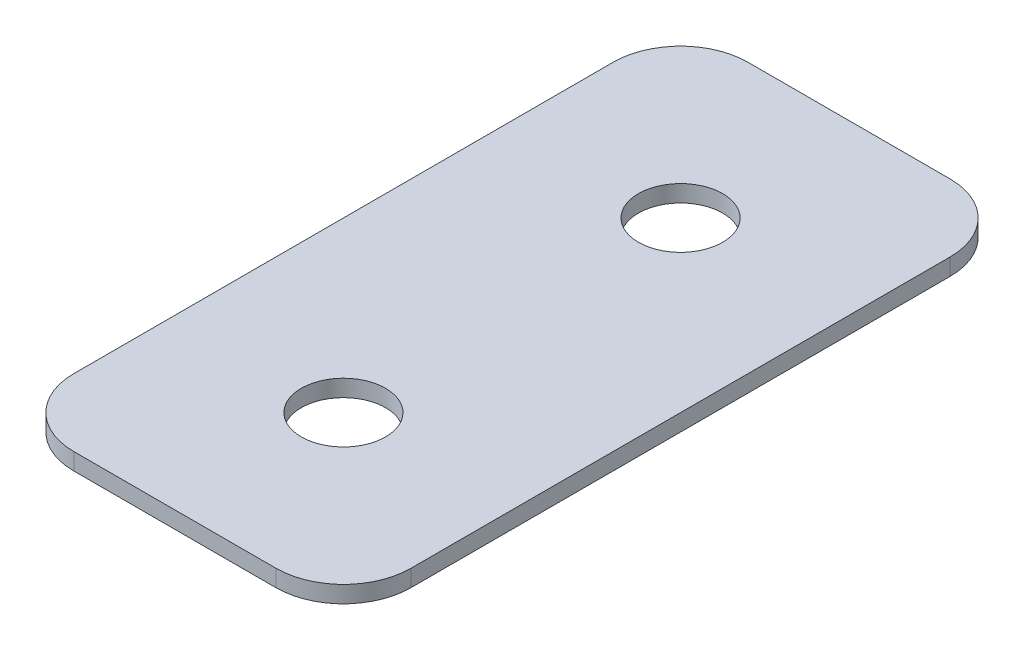
SolidWorks part; units mm, degrees
ref_plane "前视基准面" through (0, 0, 0) normal (0, 0, 1) x (1, 0, 0)
ref_plane "上视基准面" through (0, 0, 0) normal (0, 1, 0) x (1, 0, 0)
ref_plane "右视基准面" through (0, 0, 0) normal (1, 0, 0) x (0, 0, -1)
sketch "草图1" plane through (0, 0, 0) normal (0, 1, 0) x (1, 0, 0)
  line L0 (-4, 0) -> (-16, 0)
  line L1 (-20, 4) -> (-20, 36)
  line L2 (-16, 40) -> (-4, 40)
  line L3 (0, 36) -> (0, 4)
  line L4 (-20, 20) -> (0, 20) construction
  arc A0 (0, 4) -> (-4, 0) centre (-4, 4) cw
  arc A1 (0, 36) -> (-4, 40) centre (-4, 36) ccw
  arc A2 (-16, 40) -> (-20, 36) centre (-16, 36) ccw
  arc A3 (-20, 4) -> (-16, 0) centre (-16, 4) ccw
  circle A4 centre (-10, 10) radius 2.5
  circle A5 centre (-10, 30) radius 2.5
  point P7 (0, 0)
  point P12 (-20, 40)
  point P15 (-20, 0)
  point P22 (0, 0)
  point P23 (-12.6449, 10)
  point P24 (-10, 29.1941)
  dimension "D3" = 4
  dimension "D4" = 10
  dimension "D1" = 20
  dimension "D2" = 40
  dimension "D5" = 10
  dimension "D6" = 20
extrude "凸台-拉伸2" add sketch "草图1" along normal blind 1
